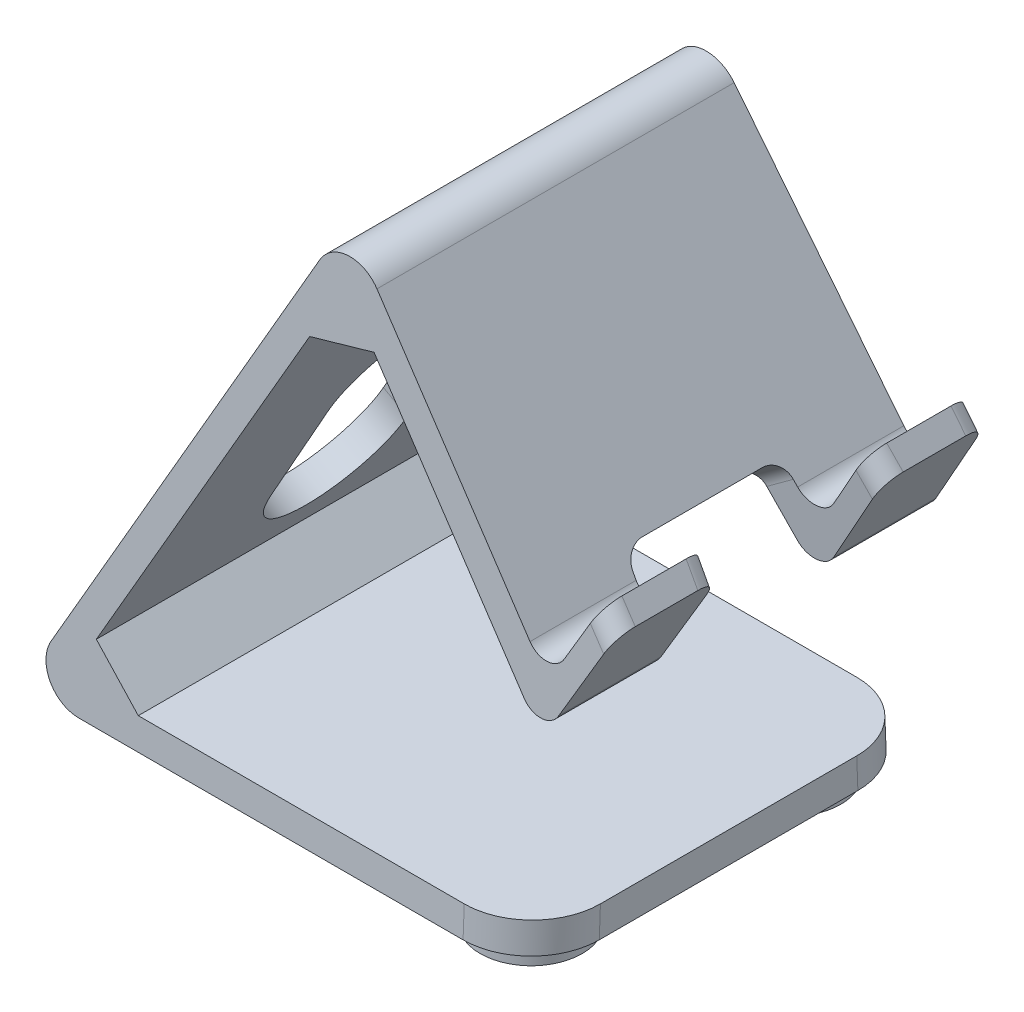
SolidWorks part; units mm, degrees
ref_plane "前视基准面" through (0, 0, 0) normal (0, 0, 1) x (1, 0, 0)
ref_plane "上视基准面" through (0, 0, 0) normal (0, 1, 0) x (1, 0, 0)
ref_plane "右视基准面" through (0, 0, 0) normal (1, 0, 0) x (0, 0, -1)
sketch "草图1" plane through (0, 0, 0) normal (0, 0, 1) x (1, 0, 0)
  line L0 (0, 0) -> (-75, 0)
  line L1 (-75, 0) -> (-30, 80)
  line L2 (-30, 80) -> (1, 37.6)
  line L3 (1, 37.6) -> (8.5, 50.5904)
  line L4 (8.5, 50.5904) -> (10.5657, 47.765)
  line L5 (10.5657, 47.765) -> (0.4336, 30.2157)
  line L6 (0.4336, 30.2157) -> (-30, 71.8411)
  line L7 (-30, 71.8411) -> (-67.8794, 4.5)
  line L8 (-67.8794, 4.5) -> (0, 4.5)
  line L9 (0, 4.5) -> (0, 0)
  point P4 (0, 0)
  point P12 (0, 0)
  point P13 (-77.1951, -0.5488)
  point P14 (-77.1951, 1.6463)
  point P15 (-1.9358, 77.9352)
  point P16 (0, 0)
  point P17 (0, 0)
  point P18 (-25.5045, 59.5263)
  point P19 (-49.9886, 26.931)
  point P20 (0, 0)
  point P21 (0, 0)
  point P22 (0, 0)
  point P23 (12, 75.0925)
  point P24 (12, 75.0925)
  point P25 (0, 0)
  point P26 (0, 0)
  point P27 (0, 0)
  point P28 (0, 0)
  point P29 (0, 0)
  point P30 (0, 0)
  dimension "D1" = 75
  dimension "D2" = 80
  dimension "D3" = 45
  dimension "D4" = 31
  dimension "D5" = 15
  dimension "D6" = 60
  dimension "D7" = 3.5
  dimension "D8" = 31
  dimension "D9" = 4.5
  dimension "D10" = 4
  dimension "D11" = 37.6
extrude "凸台-拉伸1" add sketch "草图1" along normal mid plane 58
sketch "草图2" plane through (0, 0, 0) normal (1, 0, 0) x (0, 0, -1)
  line L0 (-29, 0) -> (-26, 80)
  line L1 (-29, 80) -> (29, 80) construction
  line L2 (-26, 80) -> (-29, 80)
  line L3 (-29, 80) -> (-29, 0)
  line L4 (0, 0) -> (0, 80) construction
  line L5 (-29, 0) -> (29, 0) construction
  line L6 (29, 80) -> (29, 0)
  line L7 (26, 80) -> (29, 80)
  line L8 (29, 0) -> (26, 80)
  dimension "D1" = 52
extrude "切除-拉伸1" cut sketch "草图2" against normal through all both and the other way through all
sketch "草图3" plane through (18.566, 13.5742, 0) normal (0.8073, 0.5902, 0) x (0, 0, -1)
  line L0 (0, 0) -> (0, 38) construction
  line L1 (11.5, 38) -> (-11.5, 38)
  line L2 (-11.5, 38) -> (-14, 13)
  line L3 (-14, 13) -> (14, 13)
  line L4 (11.5, 38) -> (14, 13)
  line L5 (-29, 0) -> (29, 0) construction
  point P7 (0, 13)
  dimension "D1" = 13
  dimension "D2" = 25
  dimension "D3" = 23
  dimension "D4" = 28
extrude "切除-拉伸2" cut sketch "草图3" against normal up to next and the other way through all
fillet "圆角2" radius 10 2 edges at (0, 2.25, -28.9156) (0, 2.25, 28.9156)
chamfer "倒角1" distance 10 angle 45 2 edges at (-30, 71.8411, 0) (-67.8794, 4.5, 0)
fillet "圆角4" radius 5 1 edges at (-75, 0, 0)
fillet "圆角5" radius 5 1 edges at (-30, 80, 0)
fillet "圆角6" radius 3 4 edges at (0.4336, 30.2157, -20.3767) (0.4336, 30.2157, 20.3767) (1, 37.6, -19.9569) (1, 37.6, 19.9569)
fillet "圆角8" radius 3 4 edges at (9.5329, 49.1777, -27.1558) (9.5329, 49.1777, -11.8928) (9.5329, 49.1777, 11.8928) (9.5329, 49.1777, 27.1558)
sketch "草图4" plane through (0, 0, 0) normal (0, -1, 0) x (1, 0, 0)
  line L0 (0, 0) -> (-60, 0)
  line L1 (0, 18.993) -> (0, -18.993) construction
  circle A0 centre (-10, 18.993) radius 7.5
  circle A1 centre (-10, -18.993) radius 7.5
  circle A2 centre (-60, 0) radius 7.5
  ellipse E0 centre (-10, 18.993) end of major axis (-10, 29) minor radius 10 (0, 18.993) -> (-10, 29) ccw construction
  ellipse E1 centre (-10, -18.993) end of major axis (-10, -8.9859) minor radius 10 (-10, -29) -> (0, -18.993) ccw construction
  point P9 (0, 0)
  dimension "D2" = 15
  dimension "D3" = 15
  dimension "D4" = 15
  dimension "D1" = 60
extrude "凸台-拉伸2" add sketch "草图4" along normal blind 3 contours A1 | A2 | A0
sketch "草图5" plane through (-56.9733, 32.0475, 0) normal (-0.8716, 0.4903, 0) x (0, 0, 1)
  line L0 (0, -33.2204) -> (0, 52.2492) construction
  line L1 (-28.9759, -33.2204) -> (28.9759, -33.2204) construction
  line L2 (26.1824, 52.2492) -> (-26.1824, 52.2492) construction
  line L3 (0, 9.5144) -> (0, -7.5981) construction
  line L4 (10, 9.5144) -> (10, -7.5981)
  line L5 (-10, 9.5144) -> (-10, -7.5981)
  arc A0 (10, 9.5144) -> (-10, 9.5144) centre (0, 9.5144) ccw
  arc A1 (-10, -7.5981) -> (10, -7.5981) centre (0, -7.5981) ccw
  point P8 (0, 0.9582)
  point P13 (0, 0)
  dimension "D1" = 17.1126
  dimension "D2" = 20
extrude "切除-拉伸3" cut sketch "草图5" against normal blind 9
sketch "草图6" plane through (-56.9733, 32.0475, 0) normal (-0.8716, 0.4903, 0) x (0, 0, 1)
  text T0 "phone stand\r\n"
extrude "切除-拉伸4" cut sketch "草图6" against normal blind 0.3
fillet "圆角9" radius 3 2 edges at (-5.8055, 42.8287, -11.5) (-5.8055, 42.8287, 11.5)
